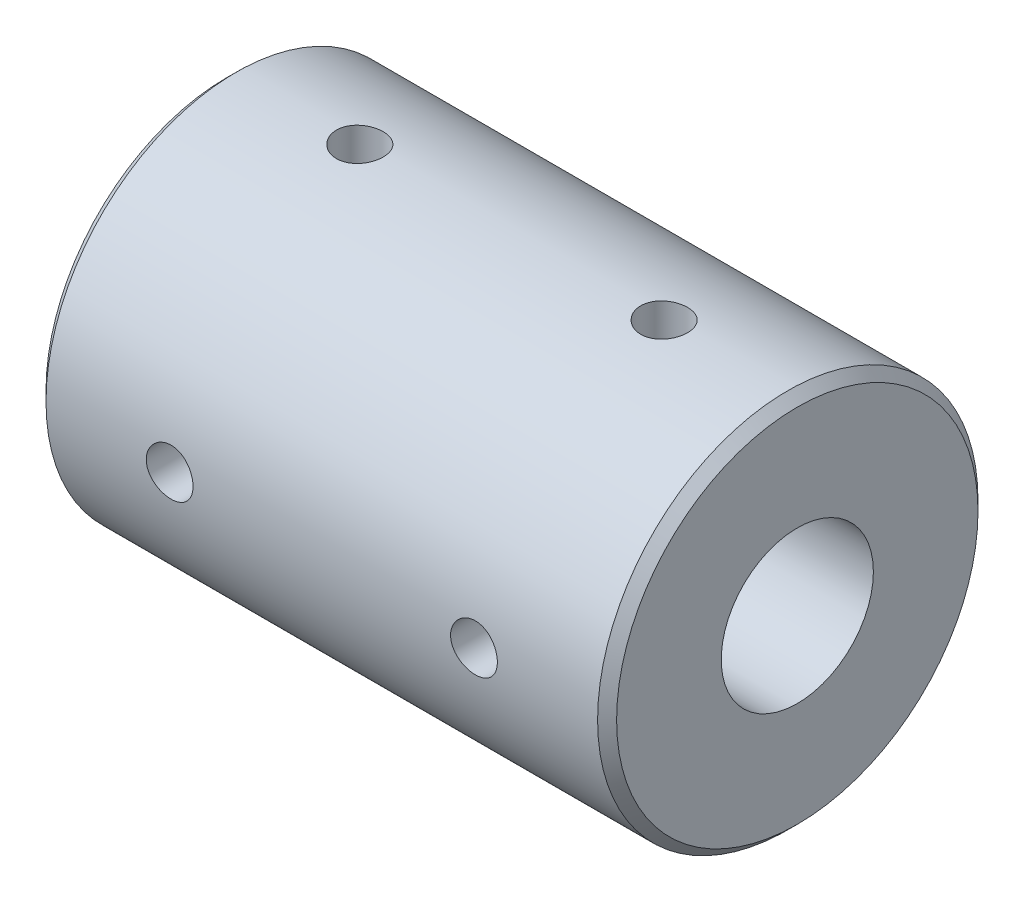
SolidWorks part; units mm, degrees
ref_plane "Front Plane" through (0, 0, 0) normal (0, 0, 1) x (1, 0, 0)
ref_plane "Top Plane" through (0, 0, 0) normal (0, 1, 0) x (1, 0, 0)
ref_plane "Right Plane" through (0, 0, 0) normal (1, 0, 0) x (0, 0, -1)
ref_plane "Plane1" through (30, 0, 0) normal (1, 0, 0) x (0, 0, -1)
sketch "Sketch1" plane through (0, 0, 0) normal (0, 0, 1) x (1, 0, 0)
  line L0 (0, 0) -> (30, 0)
  line L1 (0, 0) -> (30, 0) construction
  line L2 (0, 0) -> (0, 10)
  line L3 (0, 10) -> (30, 10)
  line L4 (30, 0) -> (30, 10)
  dimension "L" = 30
  dimension "D" = 20
revolve "Revolve1" add sketch "Sketch1" angle 360 about L1
sketch "Sketch2" plane through (0, 0, 0) normal (1, 0, 0) x (0, 0, -1)
  circle A0 centre (0, 0) radius 2.5
  dimension "D1_s" = 5
extrude "Cut-Extrude1" cut sketch "Sketch2" along normal blind 15
sketch "Sketch3" plane through (30, 0, 0) normal (1, 0, 0) x (0, 0, -1)
  circle A0 centre (0, 0) radius 4
  dimension "D2_s" = 8
extrude "Cut-Extrude2" cut sketch "Sketch3" against normal blind 15
ref_plane "Plane2" through (0, 0, 10) normal (0, 0, 1) x (1, 0, 0)
hole_wizard "Tap1" positions "Sketch5" profile "Sketch4" hole size "M3x0.5" standard "JIS"
sketch "Sketch5" plane through (0, 0, 10) normal (0, 0, 1) x (1, 0, 0)
  line L0 (30, -8.8) -> (30, 8.8) construction
  point P0 (7, 0)
  point P2 (23, 0)
  dimension "F" = 7
  dimension "FIX_6" = 7
sketch "Sketch4" plane through (7, 0, 10) normal (1, 0, 0) x (0, -1, 0)
  line L0 (0, 0) -> (0, 7.5)
  line L1 (0, 7.5) -> (1.2295, 7.5)
  line L2 (1.2295, 7.5) -> (1.2295, 0)
  line L5 (1.2295, 0) -> (0, 0)
  line L11 (0, -6.35) -> (0, 107.95) construction
  dimension "Thru Hole Depth" = 7.5
  dimension "STD" = 2.459
cosmetic thread "Thread1" parameters "M"=3
cosmetic thread "Thread2" parameters "M"=3
ref_plane "Plane3" through (0, 10, 0) normal (0, 1, 0) x (1, 0, 0)
hole_wizard "Tap2" positions "Sketch7" profile "Sketch6" hole size "M3x0.5" standard "JIS"
sketch "Sketch7" plane through (0, 10, 0) normal (0, 1, 0) x (1, 0, 0)
  line L0 (30, -8.8) -> (30, 8.8) construction
  point P0 (7, 0)
  point P2 (23, 0)
  dimension "F" = 7
  dimension "FIX_7" = 7
sketch "Sketch6" plane through (7, 10, 0) normal (1, 0, 0) x (0, 0, 1)
  line L0 (0, 0) -> (0, 7.5)
  line L1 (0, 7.5) -> (1.2295, 7.5)
  line L2 (1.2295, 7.5) -> (1.2295, 0)
  line L5 (1.2295, 0) -> (0, 0)
  line L11 (0, -6.35) -> (0, 107.95) construction
  dimension "Thru Hole Depth" = 7.5
  dimension "STD" = 2.459
cosmetic thread "Thread3" parameters "M"=3
cosmetic thread "Thread4" parameters "M"=3
chamfer "Chamfer1" distance 0.5 2 edges at (30, 0, 10) (0, 0, 10)
equation "\"FIX_5@Cut-Extrude2\"= \"L@Plane1\" / 2"
equation "\"FIX_6@Sketch5\"= \"F@Sketch5\""
equation "\"FIX_1\"= \"D@Sketch1\" / 2"
equation "\"FIX_2\"= \"L@Plane1\" / 2"
equation "\"FIX_7@Sketch7\" = \"F@Sketch7\""
equation "\"FIX_4@Cut-Extrude1\" = \"L@Plane1\" / 2"
